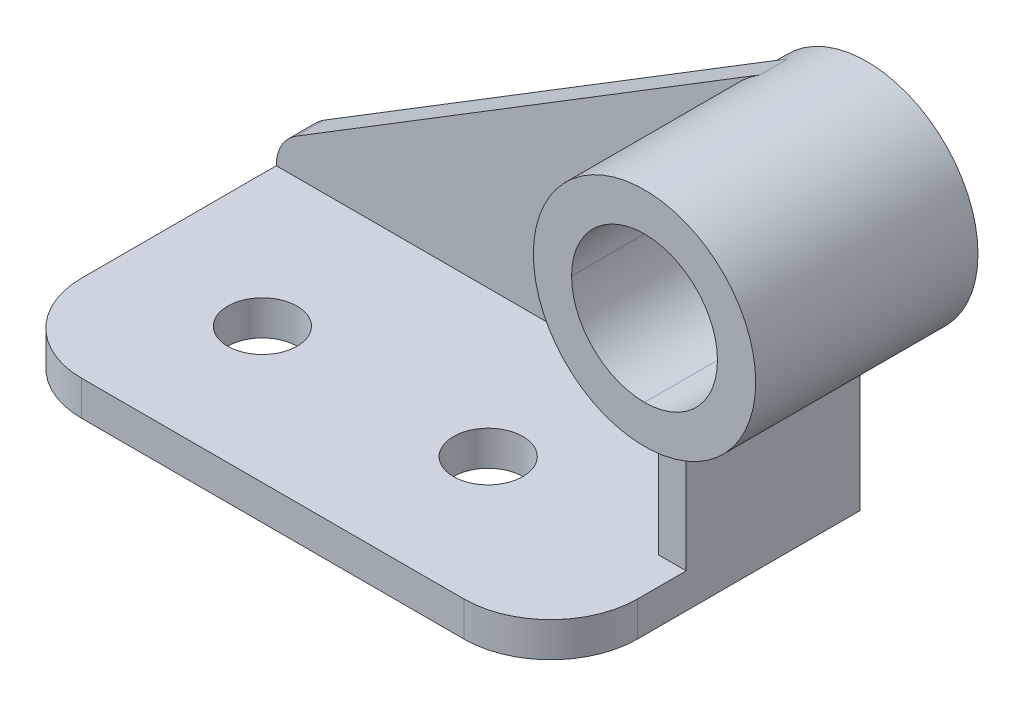
SolidWorks part; units mm, degrees
material "Alloy Steel"
ref_plane "Front" through (0, 0, 0) normal (0, 0, 1) x (1, 0, 0)
ref_plane "Top" through (0, 0, 0) normal (0, 1, 0) x (1, 0, 0)
ref_plane "Right" through (0, 0, 0) normal (1, 0, 0) x (0, 0, -1)
sketch "Sketch1" plane through (0, 0, 0) normal (0, 1, 0) x (1, 0, 0)
  line L0 (25, 0) -> (135, 0)
  line L1 (0, 25) -> (0, 89)
  line L2 (160, 89) -> (0, 89)
  line L3 (160, 89) -> (160, 25)
  arc A0 (25, 0) -> (0, 25) centre (25, 25) cw
  arc A1 (160, 25) -> (135, 0) centre (135, 25) cw
  dimension "D1" = 25
  dimension "D2" = 25
  dimension "D3" = 89
  dimension "D4" = 160
extrude "Base-Extrude" add sketch "Sketch1" along normal blind 10
sketch "Sketch2" plane through (0, 0, -89) normal (0, 0, -1) x (-1, 0, 0)
  line L0 (-160, 0) -> (0, 0) construction
  line L1 (0, 10) -> (0, 0) construction
  line L2 (-160, 10) -> (0, 10) construction
  line L3 (-160, 10) -> (0, 10)
  line L4 (-160, 10) -> (-160, 0) construction
  line L5 (-160, 10) -> (-160, 43.251)
  line L6 (-5.7182, 20.2244) -> (-139.2484, 102.2651)
  arc A0 (-139.2484, 102.2651) -> (-160, 43.251) centre (-156, 75) ccw
  arc A1 (0, 10) -> (-5.7182, 20.2244) centre (-12, 10) ccw
  dimension "D1" = 64
  dimension "D4" = 12
  dimension "D2" = 75
  dimension "D3" = 156
extrude "Boss-Extrude1" add sketch "Sketch2" against normal blind 8
ref_plane "Plane4" through (0, 0, -95) normal (0, 0, -1) x (-1, 0, 0)
sketch "Sketch3" plane through (0, 0, -95) normal (0, 0, -1) x (-1, 0, 0)
  circle A0 centre (-156, 75) radius 32
  arc A1 (-139.2484, 102.2651) -> (-160, 43.251) centre (-156, 75) ccw construction
extrude "Boss-Extrude2" add sketch "Sketch3" against normal blind 64
sketch "Sketch7" plane through (0, 0, -95) normal (0, 0, -1) x (-1, 0, 0)
  circle A0 centre (-156, 75) radius 21
  dimension "D1" = 42
extrude "Cut-Extrude1" cut sketch "Sketch7" against normal through all
sketch "Sketch4" plane through (0, 10, 0) normal (0, 1, 0) x (-1, 0, 0)
  line L1 (-152, -81) -> (-152, -25)
  line L2 (-152, -81) -> (-152, -39)
  line L3 (-160, -39) -> (0, -39)
  line L4 (-160, -81) -> (-160, -25) construction
  line L5 (-160, -81) -> (-160, -39)
  line L6 (-160, -81) -> (0, -81) construction
  line L7 (-160, -81) -> (-152, -81)
  line L8 (-160, -39) -> (-152, -39)
  dimension "D1" = 8
  dimension "D2" = 50
extrude "Boss-Extrude3" add sketch "Sketch4" along normal up to next
hole_wizard "Hole1" positions "Sketch5" profile "Sketch6" legacy end condition through all
sketch "Sketch5" plane through (0, 10, 0) normal (0, 1, 0) x (-1, 0, 0)
  line L0 (0, -25) -> (0, -81) construction
  line L2 (-5.7182, -89) -> (-139.2484, -89) construction
  point P0 (-38, -39)
  dimension "D1" = 38
  dimension "D2" = 50
sketch "Sketch6" plane through (38, 10, -39) normal (1, 0, 0) x (0, 0, 1)
  line L0 (0, 0) -> (0, 10)
  line L1 (0, 10) -> (10, 10)
  line L2 (10, 10) -> (10, 0)
  line L3 (10, 0) -> (0, 0)
pattern_linear "LPattern1" count 2 spacing 65 along (1, 0, 0) of "Hole1"
ref_plane "Plane5" through (0, 75, 0) normal (0, 1, 0) x (-1, 0, 0)
sketch "Sketch9" plane through (0, 75, 0) normal (0, 1, 0) x (-1, 0, 0)
  line L0 (-156, -31) -> (-156, -95)
  line L1 (-135, -31) -> (-177, -31) construction
  line L2 (-124, -95) -> (-188, -95) construction
split line "Split Line1"
ref_plane "Plane7" through (156, 0, 0) normal (1, 0, 0) x (0, 0, -1)
sketch "Sketch14" plane through (156, 0, 0) normal (1, 0, 0) x (0, 0, -1)
  line L2 (31, 75) -> (95, 75)
  line L3 (31, 107) -> (31, 43) construction
  line L4 (95, 107) -> (95, 43) construction
split line "Split Line2"
